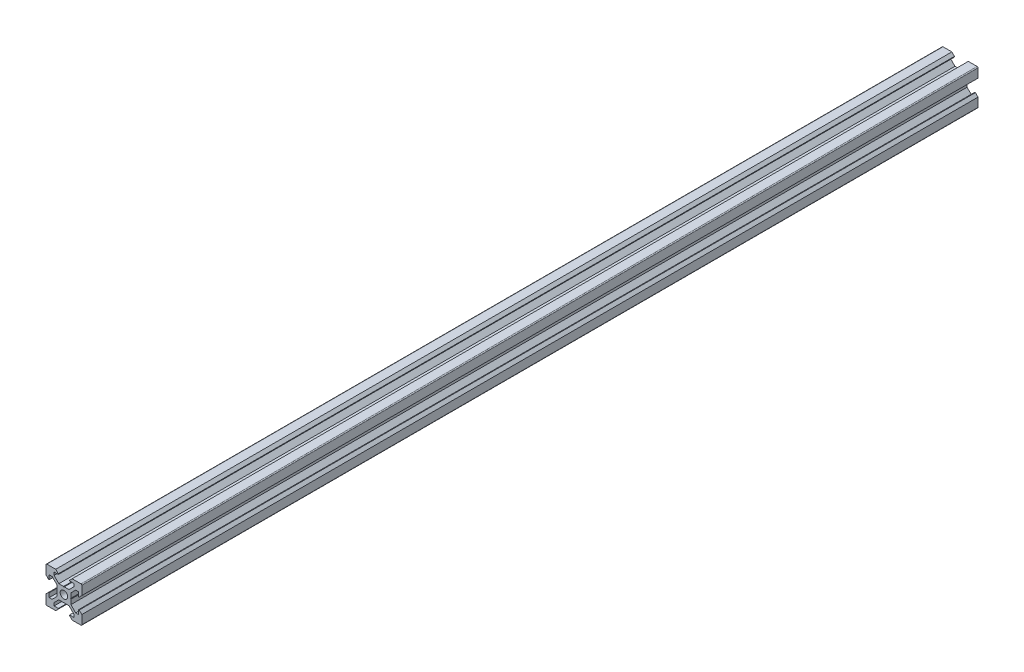
SolidWorks part; units mm, degrees
ref_plane "Front Plane" through (0, 0, 0) normal (0, 0, 1) x (1, 0, 0)
ref_plane "Top Plane" through (0, 0, 0) normal (0, 1, 0) x (1, 0, 0)
ref_plane "Right Plane" through (0, 0, 0) normal (1, 0, 0) x (0, 0, -1)
ref_plane "Plane1" through (0, 0, 0) normal (0, 0, -1) x (-1, 0, 0)
sketch "Sketch1" plane through (0, 0, 0) normal (0, 0, -1) x (-1, 0, 0)
  line L0 (-3.69, 0) -> (-3.9, -0.21)
  line L1 (-3.9, -0.21) -> (-3.9, -2.8393)
  line L2 (-3.9, -2.8393) -> (-6.5607, -5.5)
  line L3 (-6.5607, -5.5) -> (-8.2, -5.5)
  line L4 (-8.2, -5.5) -> (-8.2, -3.125)
  line L5 (-8.2, -3.125) -> (-8.545, -3.125)
  line L6 (-8.545, -3.125) -> (-10, -4.58)
  line L7 (-10, -4.58) -> (-10, -9.5)
  line L8 (-9.5, -10) -> (-4.58, -10)
  line L9 (-4.58, -10) -> (-3.125, -8.545)
  line L10 (-3.125, -8.545) -> (-3.125, -8.2)
  line L11 (-3.125, -8.2) -> (-5.5, -8.2)
  line L12 (-5.5, -8.2) -> (-5.5, -6.5607)
  line L13 (-5.5, -6.5607) -> (-2.8393, -3.9)
  line L14 (-2.8393, -3.9) -> (-0.21, -3.9)
  line L15 (-0.21, -3.9) -> (0, -3.69)
  line L16 (0, -3.69) -> (0.21, -3.9)
  line L17 (0.21, -3.9) -> (2.8393, -3.9)
  line L18 (2.8393, -3.9) -> (5.5, -6.5607)
  line L19 (5.5, -6.5607) -> (5.5, -8.2)
  line L20 (5.5, -8.2) -> (3.125, -8.2)
  line L21 (3.125, -8.2) -> (3.125, -8.545)
  line L22 (3.125, -8.545) -> (4.58, -10)
  line L23 (4.58, -10) -> (9.5, -10)
  line L24 (10, -9.5) -> (10, -4.58)
  line L25 (10, -4.58) -> (8.545, -3.125)
  line L26 (8.545, -3.125) -> (8.2, -3.125)
  line L27 (8.2, -3.125) -> (8.2, -5.5)
  line L28 (8.2, -5.5) -> (6.5607, -5.5)
  line L29 (6.5607, -5.5) -> (3.9, -2.8393)
  line L30 (3.9, -2.8393) -> (3.9, -0.21)
  line L31 (3.9, -0.21) -> (3.69, 0)
  line L32 (3.69, 0) -> (3.9, 0.21)
  line L33 (3.9, 0.21) -> (3.9, 2.8393)
  line L34 (3.9, 2.8393) -> (6.5607, 5.5)
  line L35 (6.5607, 5.5) -> (8.2, 5.5)
  line L36 (8.2, 5.5) -> (8.2, 3.125)
  line L37 (8.2, 3.125) -> (8.545, 3.125)
  line L38 (8.545, 3.125) -> (10, 4.58)
  line L39 (10, 4.58) -> (10, 9.5)
  line L40 (9.5, 10) -> (4.58, 10)
  line L41 (4.58, 10) -> (3.125, 8.545)
  line L42 (3.125, 8.545) -> (3.125, 8.2)
  line L43 (3.125, 8.2) -> (5.5, 8.2)
  line L44 (5.5, 8.2) -> (5.5, 6.5607)
  line L45 (5.5, 6.5607) -> (2.8393, 3.9)
  line L46 (2.8393, 3.9) -> (0.21, 3.9)
  line L47 (0.21, 3.9) -> (0, 3.69)
  line L48 (0, 3.69) -> (-0.21, 3.9)
  line L49 (-0.21, 3.9) -> (-2.8393, 3.9)
  line L50 (-2.8393, 3.9) -> (-5.5, 6.5607)
  line L51 (-5.5, 6.5607) -> (-5.5, 8.2)
  line L52 (-5.5, 8.2) -> (-3.125, 8.2)
  line L53 (-3.125, 8.2) -> (-3.125, 8.545)
  line L54 (-3.125, 8.545) -> (-4.58, 10)
  line L55 (-4.58, 10) -> (-9.5, 10)
  line L56 (-10, 9.5) -> (-10, 4.58)
  line L57 (-10, 4.58) -> (-8.545, 3.125)
  line L58 (-8.545, 3.125) -> (-8.2, 3.125)
  line L59 (-8.2, 3.125) -> (-8.2, 5.5)
  line L60 (-8.2, 5.5) -> (-6.5607, 5.5)
  line L61 (-6.5607, 5.5) -> (-3.9, 2.8393)
  line L62 (-3.9, 2.8393) -> (-3.9, 0.21)
  line L63 (-3.9, 0.21) -> (-3.69, 0)
  circle A0 centre (0, 0) radius 2.1
  arc A1 (-10, -9.5) -> (-9.5, -10) centre (-9.5, -9.5) ccw
  arc A2 (9.5, -10) -> (10, -9.5) centre (9.5, -9.5) ccw
  arc A3 (10, 9.5) -> (9.5, 10) centre (9.5, 9.5) ccw
  arc A4 (-9.5, 10) -> (-10, 9.5) centre (-9.5, 9.5) ccw
extrude "Boss-Extrude1" add sketch "Sketch1" against normal blind 500
